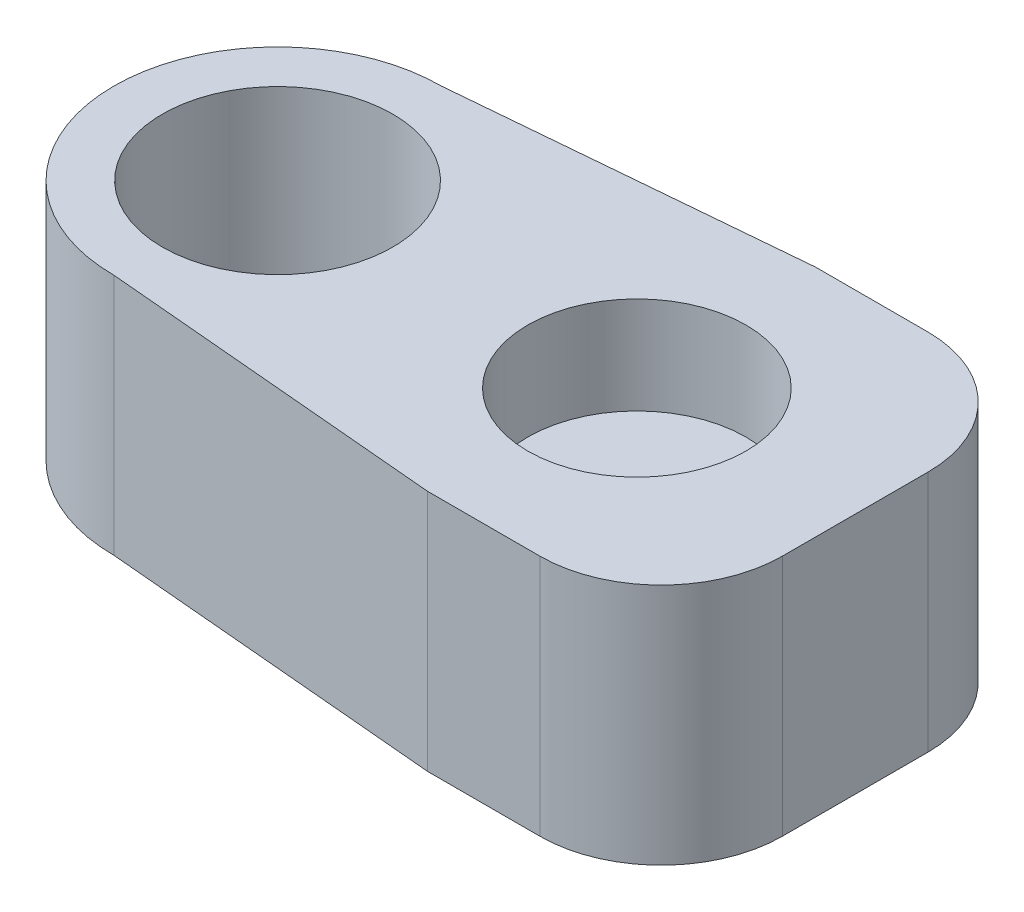
SolidWorks part; units mm, degrees
ref_plane "Piano frontale" through (0, 0, 0) normal (0, 0, 1) x (1, 0, 0)
ref_plane "Piano superiore" through (0, 0, 0) normal (0, 1, 0) x (1, 0, 0)
ref_plane "Piano destro" through (0, 0, 0) normal (1, 0, 0) x (0, 0, -1)
sketch "Sketch1" plane through (0, 0, 0) normal (0, 1, 0) x (1, 0, 0)
  line L3 (5.6491, 8) -> (10.28, 8)
  line L4 (15.28, -3) -> (15.28, 3)
  line L6 (5.6491, -8) -> (-8.53, -6.75)
  line L8 (-8.53, 0) -> (6.28, 0)
  line L11 (-8.53, 4.75) -> (-8.53, 6.75)
  line L12 (5.6491, 8) -> (-8.53, 6.75)
  line L13 (5.6491, -8) -> (10.28, -8)
  circle A0 centre (-8.53, 0) radius 4.75
  arc A5 (15.28, 3) -> (10.28, 8) centre (10.28, 3) ccw
  arc A6 (-8.53, 6.75) -> (-15.28, 0) centre (-8.53, 0) ccw
  arc A7 (-8.53, -6.75) -> (-15.28, 0) centre (-8.53, 0) cw
  arc A8 (15.28, -3) -> (10.28, -8) centre (10.28, -3) cw
  point P0 (0, 0)
  dimension "D3" = 14.81
  dimension "D4" = 5
  dimension "D1" = 6.75
  dimension "D2" = 9.5
  dimension "D5" = 9
extrude "Boss-Extrude1" add sketch "Sketch1" along normal blind 10
sketch "Sketch2" plane through (0, 10, 0) normal (0, 1, 0) x (1, 0, 0)
  line L0 (-8.53, 0) -> (6.28, 0)
  circle A0 centre (6.28, 0) radius 4.5
extrude "Cut-Extrude1" cut sketch "Sketch2" against normal blind 4
sketch "Sketch4" plane through (0, 0, 0) normal (0, -1, 0) x (1, 0, 0)
  line L0 (-8.53, 0) -> (6.28, 0)
  circle A0 centre (6.28, 0) radius 4.5
extrude "Cut-Extrude2" cut sketch "Sketch4" against normal blind 4
